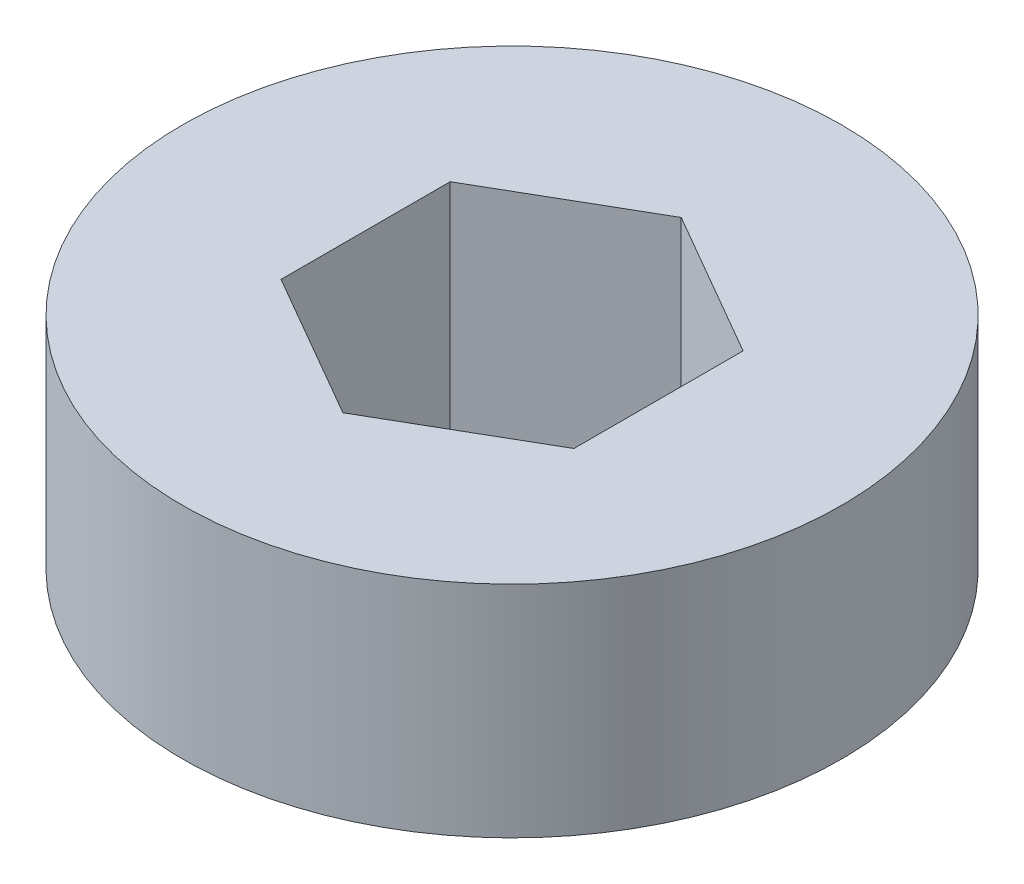
SolidWorks part; units mm, degrees
ref_plane "Front Plane" through (0, 0, 0) normal (0, 0, 1) x (1, 0, 0)
ref_plane "Top Plane" through (0, 0, 0) normal (0, 1, 0) x (1, 0, 0)
ref_plane "Right Plane" through (0, 0, 0) normal (1, 0, 0) x (0, 0, -1)
sketch "Sketch1" plane through (0, 0, 0) normal (0, 1, 0) x (1, 0, 0)
  line L1 (6.35, -3.6662) -> (6.35, 3.6662)
  line L2 (6.35, 3.6662) -> (0, 7.3323)
  line L3 (0, 7.3323) -> (-6.35, 3.6662)
  line L4 (-6.35, 3.6662) -> (-6.35, -3.6662)
  line L5 (-6.35, -3.6662) -> (0, -7.3323)
  line L6 (0, -7.3323) -> (6.35, -3.6662)
  circle A0 centre (0, 0) radius 6.35 construction
  circle A1 centre (0, 0) radius 14.2875
  point P10 (0, -14.2875)
  dimension "D1" = 28.575
  dimension "D2" = 12.7
extrude "Boss-Extrude1" add sketch "Sketch1" along normal blind 9.525
